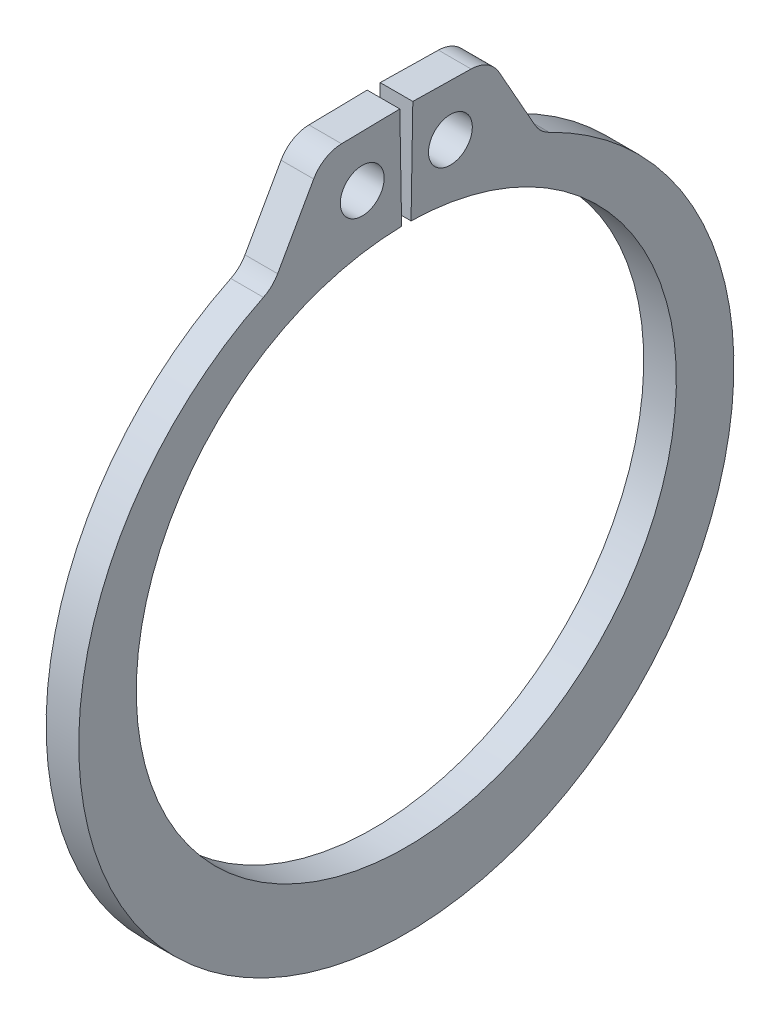
SolidWorks part; units mm, degrees
material "Cast Carbon Steel"
ref_plane "Front" through (0, 0, 0) normal (0, 0, 1) x (1, 0, 0)
ref_plane "Top" through (0, 0, 0) normal (0, 1, 0) x (1, 0, 0)
ref_plane "Right" through (0, 0, 0) normal (1, 0, 0) x (0, 0, -1)
sketch "Sketch1" plane through (0, 0, 0) normal (1, 0, 0) x (0, 0, -1)
  line L0 (0, 0) -> (0, 7.3533) construction
  line L1 (-0.1283, 7.3522) -> (-0.1771, 10.1458)
  line L2 (0.1771, 10.1458) -> (2.2723, 10.1092)
  line L3 (2.2723, 10.1092) -> (3.6441, 7.6751)
  line L4 (0.1283, 7.3522) -> (0.1771, 10.1458)
  line L5 (-0.1771, 10.1458) -> (-2.2723, 10.1092)
  line L6 (-2.2723, 10.1092) -> (-3.6441, 7.6751)
  line L7 (-3.6441, 7.6751) -> (-3.1539, 6.6426) construction
  line L8 (3.6441, 7.6751) -> (3.1539, 6.6426) construction
  line L9 (0, -7.3533) -> (0, -9.3853) construction
  line L10 (-2.2723, 10.1092) -> (-0.1283, 7.3522) construction
  line L11 (0, 7.3533) -> (0, 10.1473) construction
  line L12 (-7.3533, 0) -> (7.3533, 0) construction
  circle A0 centre (0, 0) radius 7.3533 construction
  arc A1 (-0.1283, 7.3522) -> (0.1283, 7.3522) centre (0, 0) ccw
  circle A3 centre (0, 0) radius 11.43 construction
  circle A4 centre (-1.2003, 8.7307) radius 0.5969
  circle A5 centre (1.2003, 8.7307) radius 0.5969
  arc A6 (-3.6441, 7.6751) -> (3.6441, 7.6751) centre (0, -0.4659) ccw
  point P0 (0, -9.3853)
  dimension "A" = 14.7066
  dimension "Hole" = 1.1938
  dimension "Smin" = 1.143
  dimension "H" = 2.794
  dimension "D2" = 2.0955
  dimension "Angle" = 1
extrude "Extrude1" add sketch "Sketch1" along normal mid plane 0.889
fillet "Fillet1" radius 0.889 4 edges at (0, 7.6751, 3.6441) (0, 7.6751, -3.6441) (0, 10.1092, 2.2723) (0, 10.1092, -2.2723)
sketch "Sketch2" plane through (0, 0, 0) normal (0, 0, 1) x (1, 0, 0)
  line L0 (-4.9403, 0) -> (12.8397, 0)
  line L1 (12.8397, 0) -> (12.8397, -7.9375)
  line L2 (-4.9403, 0) -> (-4.9403, -7.4676)
  line L3 (12.8397, -7.9375) -> (0.4953, -7.9375)
  line L4 (0.4953, -7.9375) -> (0.4953, -7.4676)
  line L5 (0.4953, -7.4676) -> (-0.4953, -7.4676)
  line L6 (-0.4953, -7.4676) -> (-0.4953, -7.9375)
  line L7 (-0.4953, -7.9375) -> (-4.9403, -7.9375) construction
  line L8 (-4.9403, -7.9375) -> (-4.9403, 0) construction
  line L9 (12.8397, 0) -> (76.391, 0) construction
  line L10 (0, -7.4676) -> (0, 0) construction
  line L11 (-4.9403, -7.4676) -> (-4.4704, -7.9375)
  line L12 (-4.4704, -7.9375) -> (-0.4953, -7.9375)
  dimension "D2" = 17.78
  dimension "D3" = 4.445
  dimension "D1" = 45
revolve "Revolve1" [suppressed] add sketch "Sketch2" angle 360 about L9
delete or keep bodies "Body-Delete1" [suppressed] type delete bodies bodies 122
equation "\"D2@Sketch2\" = \"D1@Extrude1\"*20"
equation "\"D3@Sketch2\" = \"D2@Sketch2\"/4"
equation "\"D2@Sketch1\" = \"H@Sketch1\"*.75"
equation "\"D1@Fillet1\" = \"D1@Extrude1\""
